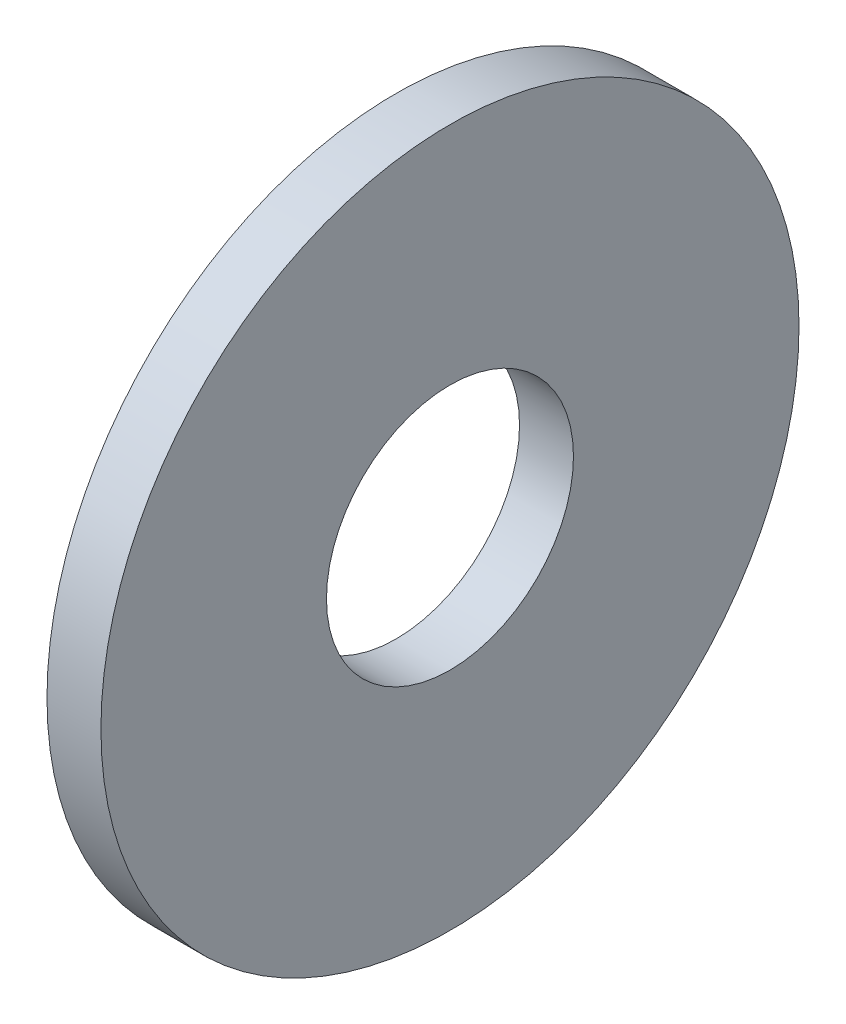
SolidWorks part; units mm, degrees
ref_plane "Plane1" through (0, 0, 0) normal (0, 0, 1) x (1, 0, 0)
ref_plane "Plane2" through (0, 0, 0) normal (0, 1, 0) x (1, 0, 0)
ref_plane "Plane3" through (0, 0, 0) normal (1, 0, 0) x (0, 0, -1)
sketch "Sketch1" plane through (0, 0, 0) normal (0, 0, 1) x (1, 0, 0)
  line L0 (-34.925, 0) -> (9.525, 0) construction
  line L1 (0, 19.46) -> (0, 55)
  line L2 (0, 55) -> (-8.5, 55)
  line L3 (-8.5, 55) -> (-8.5, 19.46)
  line L4 (-8.5, 19.46) -> (0, 19.46)
  dimension "Thickness" = 8.5
  dimension "Inside_dia" = 38.92
  dimension "Outside_dia" = 110
revolve "Base-Revolve" add sketch "Sketch1" angle 360 about L0
